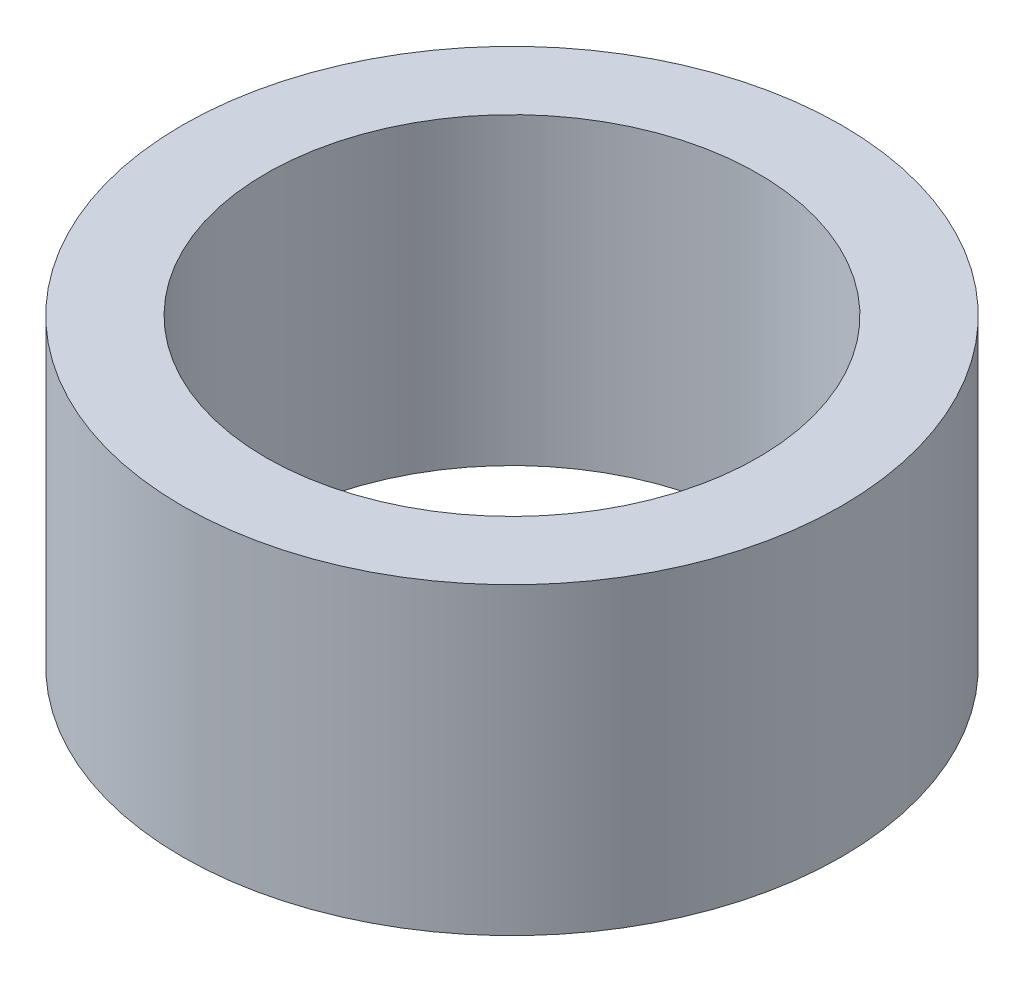
SolidWorks part; units mm, degrees
ref_plane "Front Plane" through (0, 0, 0) normal (0, 0, 1) x (1, 0, 0)
ref_plane "Top Plane" through (0, 0, 0) normal (0, 1, 0) x (1, 0, 0)
ref_plane "Right Plane" through (0, 0, 0) normal (1, 0, 0) x (0, 0, -1)
sketch "Sketch1" plane through (0, 0, 0) normal (0, 1, 0) x (1, 0, 0)
  circle A0 centre (0, 0) radius 11.825
  circle A1 centre (0, 0) radius 8.825
  dimension "D1" = 23.65
  dimension "D2" = 17.65
extrude "Boss-Extrude1" add sketch "Sketch1" against normal blind 10.9
